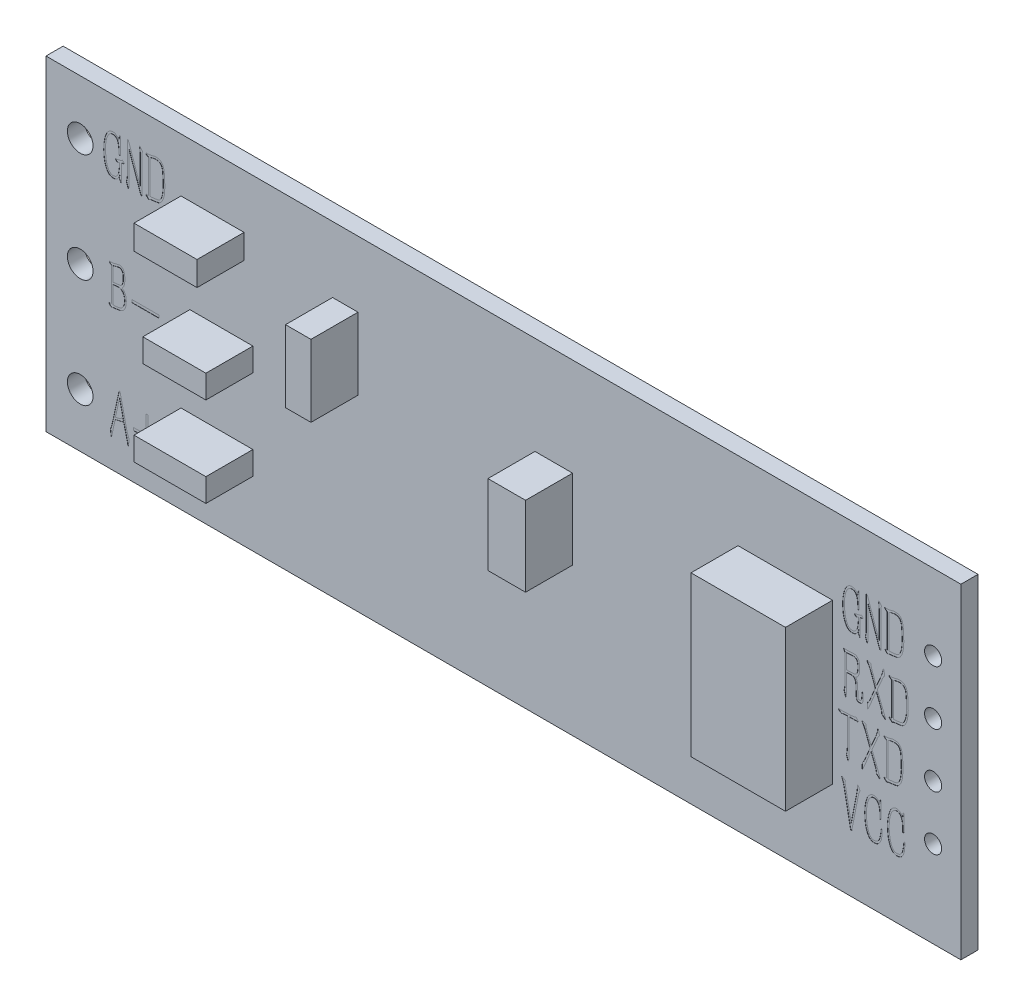
SolidWorks part; units mm, degrees
ref_plane "前视基准面" through (0, 0, 0) normal (0, 0, 1) x (1, 0, 0)
ref_plane "上视基准面" through (0, 0, 0) normal (0, 1, 0) x (1, 0, 0)
ref_plane "右视基准面" through (0, 0, 0) normal (1, 0, 0) x (0, 0, -1)
sketch "草图1" plane through (0, 0, 0) normal (0, 0, 1) x (1, 0, 0)
  line L1 (0, 0) -> (42.8, 0)
  line L2 (0, 0) -> (0, 15.22)
  line L3 (0, 15.22) -> (42.8, 15.22)
  line L4 (42.8, 0) -> (42.8, 15.22)
  dimension "D1" = 42.8
  dimension "D2" = 15.22
extrude "凸台-拉伸1" add sketch "草图1" along normal blind 0.8
sketch "草图2" plane through (0, 0, 0.8) normal (0, 0, 1) x (1, 0, 0)
  line L1 (32.3738, 11.5687) -> (36.7948, 11.5687)
  line L2 (32.3738, 11.5687) -> (32.3738, 4.1171)
  line L3 (32.3738, 4.1171) -> (36.7948, 4.1171)
  line L4 (36.7948, 11.5687) -> (36.7948, 4.1171)
  line L5 (22.8748, 10.6372) -> (24.6342, 10.6372)
  line L6 (22.8748, 10.6372) -> (22.8748, 6.9114)
  line L7 (22.8748, 6.9114) -> (24.6342, 6.9114)
  line L8 (24.6342, 10.6372) -> (24.6342, 6.9114)
  line L9 (6.3157, 12.7071) -> (9.2653, 12.7071)
  line L10 (6.3157, 12.7071) -> (6.3157, 11.5687)
  line L11 (6.3157, 11.5687) -> (9.2653, 11.5687)
  line L12 (9.2653, 12.7071) -> (9.2653, 11.5687)
  line L13 (6.7297, 8.3086) -> (9.6793, 8.3086)
  line L14 (6.7297, 8.3086) -> (6.7297, 7.2219)
  line L15 (6.7297, 7.2219) -> (9.6793, 7.2219)
  line L16 (9.6793, 8.3086) -> (9.6793, 7.2219)
  line L17 (6.3157, 4.1171) -> (9.6793, 4.1171)
  line L18 (6.3157, 4.1171) -> (6.3157, 3.0304)
  line L19 (6.3157, 3.0304) -> (9.6793, 3.0304)
  line L20 (9.6793, 4.1171) -> (9.6793, 3.0304)
  line L21 (13.4051, 12.1379) -> (14.5952, 12.1379)
  line L22 (13.4051, 12.1379) -> (13.4051, 8.7743)
  line L23 (13.4051, 8.7743) -> (14.5952, 8.7743)
  line L24 (14.5952, 12.1379) -> (14.5952, 8.7743)
extrude "凸台-拉伸2" add sketch "草图2" along normal blind 2.2
sketch "草图3" plane through (0, 0, 0.8) normal (0, 0, 1) x (1, 0, 0)
  line L0 (41.5, 11.67) -> (41.5, 4.05) construction
  line L1 (0, 0) -> (42.8, 0) construction
  line L3 (42.8, 0) -> (42.8, 15.22) construction
  circle A0 centre (41.5, 11.67) radius 0.4
  circle A1 centre (41.5, 9.13) radius 0.4
  circle A2 centre (41.5, 6.59) radius 0.4
  circle A3 centre (41.5, 4.05) radius 0.4
  dimension "D1" = 4.05
  dimension "D2" = 2.54
  dimension "D3" = 2.54
  dimension "D4" = 2.54
  dimension "D5" = 1.3
  dimension "D6" = 0.8
extrude "切除-拉伸1" cut sketch "草图3" against normal blind 2.2
sketch "草图4" plane through (0, 0, 0.8) normal (0, 0, 1) x (1, 0, 0)
  line L0 (1.6, 12.68) -> (1.6, 2.52) construction
  line L1 (0, 0) -> (42.8, 0) construction
  line L2 (42.8, 15.22) -> (0, 15.22) construction
  circle A0 centre (1.6, 12.68) radius 0.6
  circle A1 centre (1.6, 7.6) radius 0.6
  circle A2 centre (1.6, 2.52) radius 0.6
  circle A3 centre (41.5, 4.05) radius 0.4 construction
  dimension "D1" = 1.2
  dimension "D2" = 2.52
  dimension "D3" = 5.08
  dimension "D4" = 2.54
  dimension "D6" = 5.08
  dimension "D5" = 39.9
extrude "切除-拉伸2" cut sketch "草图4" against normal blind 2.2
sketch "草图5" plane through (0, 0, 0.8) normal (0, 0, 1) x (1, 0, 0)
  text T0 "A+" font "汉仪长仿宋体" height in points 8
  text T1 "B-" font "汉仪长仿宋体" height in points 8
  text T2 "GND" font "汉仪长仿宋体" height in points 8
extrude "切除-拉伸3" cut sketch "草图5" against normal blind 0.01
sketch "草图6" plane through (0, 0, 0.8) normal (0, 0, 1) x (1, 0, 0)
  text T0 "VCC" font "汉仪长仿宋体" height in points 8
  text T1 "GND" font "汉仪长仿宋体" height in points 8
  text T2 "TXD" font "汉仪长仿宋体" height in points 8
  text T3 "RXD" font "汉仪长仿宋体" height in points 8
extrude "切除-拉伸4" cut sketch "草图6" against normal blind 0.01
